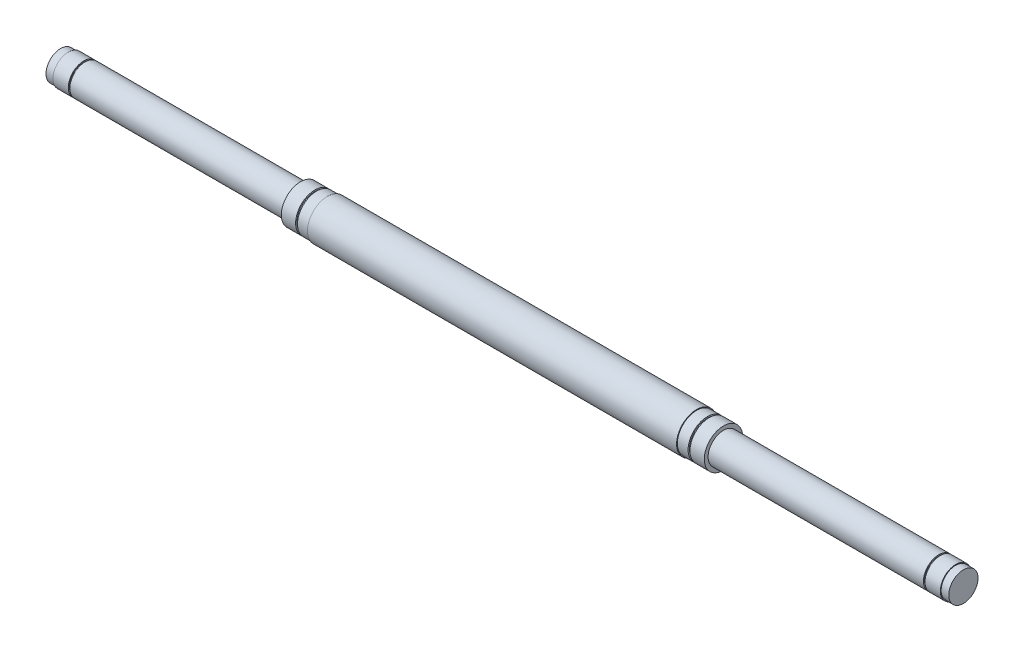
SolidWorks part; units mm, degrees
ref_plane "前视基准面" through (0, 0, 0) normal (0, 0, 1) x (1, 0, 0)
ref_plane "上视基准面" through (0, 0, 0) normal (0, 1, 0) x (1, 0, 0)
ref_plane "右视基准面" through (0, 0, 0) normal (1, 0, 0) x (0, 0, -1)
sketch "草图1" plane through (0, 0, 0) normal (0, 1, 0) x (1, 0, 0)
  line L0 (-75.6129, 0) -> (85.338, 0) construction
  line L1 (0, 103.9879) -> (0, -100.8587) construction
  line L2 (0, 0) -> (0, 9.5)
  line L3 (0, 9.5) -> (5, 9.5)
  line L4 (5, 9.5) -> (5, 10)
  line L5 (5, 10) -> (15, 10)
  line L6 (15, 10) -> (15, 9.25)
  line L7 (15, 9.25) -> (16, 9.25)
  line L8 (16, 9.25) -> (16, 10)
  line L9 (16, 10) -> (156, 10)
  line L10 (156, 10) -> (156, 12.5)
  line L11 (156, 12.5) -> (165.3, 12.5)
  line L12 (165.3, 12.5) -> (165.3, 11.6)
  line L13 (165.3, 11.6) -> (166.5, 11.6)
  line L14 (166.5, 11.6) -> (166.5, 12.5)
  line L15 (166.5, 12.5) -> (173.5, 12.5)
  line L16 (173.5, 12.5) -> (173.5, 13)
  line L17 (173.5, 13) -> (413.5, 13)
  line L18 (293.5, 13) -> (293.5, 25.841) construction
  line L19 (587, 0) -> (587, 9.5)
  line L20 (413.5, 12.5) -> (413.5, 13)
  line L21 (420.5, 12.5) -> (413.5, 12.5)
  line L22 (420.5, 11.6) -> (420.5, 12.5)
  line L23 (421.7, 11.6) -> (420.5, 11.6)
  line L24 (421.7, 12.5) -> (421.7, 11.6)
  line L25 (431, 12.5) -> (421.7, 12.5)
  line L26 (431, 10) -> (431, 12.5)
  line L27 (571, 10) -> (431, 10)
  line L28 (571, 9.25) -> (571, 10)
  line L29 (572, 9.25) -> (571, 9.25)
  line L30 (572, 10) -> (572, 9.25)
  line L31 (582, 10) -> (572, 10)
  line L32 (582, 9.5) -> (582, 10)
  line L33 (587, 9.5) -> (582, 9.5)
  line L34 (0, 0) -> (587, 0)
  point P27 (293.5, 13)
revolve "旋转1" add sketch "草图1" angle 360 about L0
